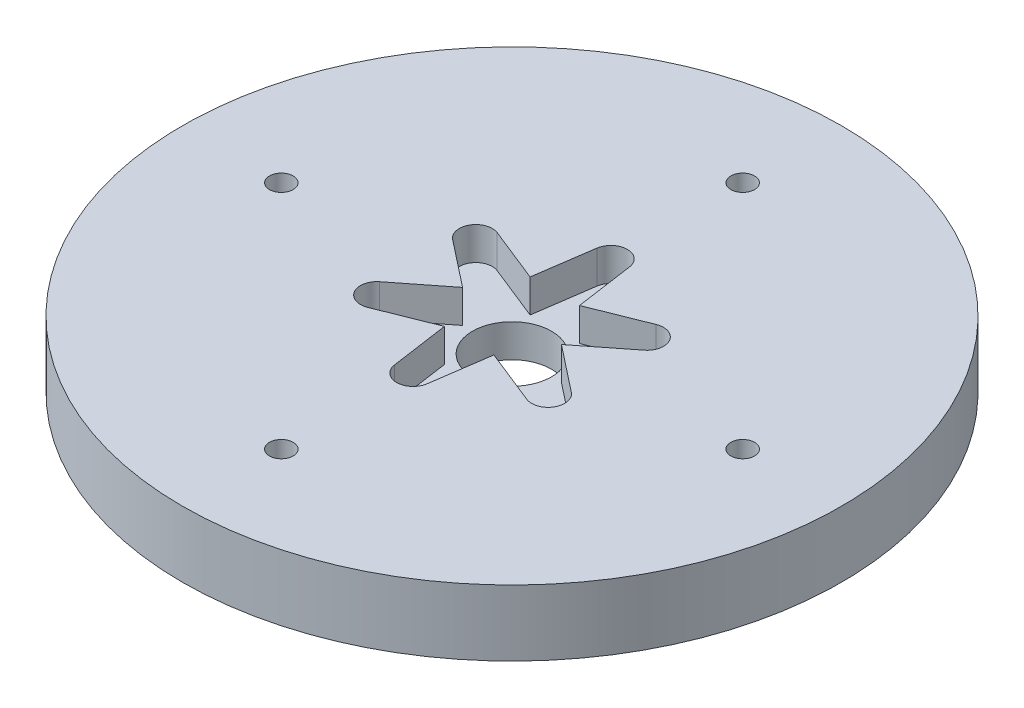
SolidWorks part; units mm, degrees
ref_plane "Front Plane" through (0, 0, 0) normal (0, 0, 1) x (1, 0, 0)
ref_plane "Top Plane" through (0, 0, 0) normal (0, 1, 0) x (1, 0, 0)
ref_plane "Right Plane" through (0, 0, 0) normal (1, 0, 0) x (0, 0, -1)
sketch "Sketch1" plane through (0, 0, 0) normal (0, 1, 0) x (1, 0, 0)
  line L0 (0, 0) -> (0, 15) construction
  line L1 (-3.75, 6.5) -> (3.75, 6.5) construction
  line L2 (-3.75, 6.5) -> (-2.4745, 15.3564)
  line L3 (2.4745, 15.3564) -> (3.75, 6.5)
  line L4 (14.5363, 5.5352) -> (7.5042, 0.0024)
  line L5 (3.7542, 6.4976) -> (12.0618, 9.8211)
  line L6 (12.0618, -9.8211) -> (3.7542, -6.4976)
  line L7 (7.5042, -0.0024) -> (14.5363, -5.5352)
  line L8 (-2.4745, -15.3564) -> (-3.75, -6.5)
  line L9 (3.75, -6.5) -> (2.4745, -15.3564)
  line L10 (-14.5363, -5.5352) -> (-7.5042, -0.0024)
  line L11 (-3.7542, -6.4976) -> (-12.0618, -9.8211)
  line L12 (-12.0618, 9.8211) -> (-3.7542, 6.4976)
  line L13 (-7.5042, 0.0024) -> (-14.5363, 5.5352)
  line L14 (3.75, 6.5) -> (3.7542, 6.4976)
  line L15 (7.5042, 0.0024) -> (7.5042, -0.0024)
  line L16 (3.7542, -6.4976) -> (3.75, -6.5)
  line L17 (-3.75, -6.5) -> (-3.7542, -6.4976)
  line L18 (-7.5042, 0.0024) -> (-7.5042, -0.0024)
  line L19 (-3.75, 6.5) -> (-3.7542, 6.4976)
  arc A0 (2.4745, 15.3564) -> (-2.4745, 15.3564) centre (0, 15) ccw
  arc A1 (14.5363, 5.5352) -> (12.0618, 9.8211) centre (12.9904, 7.5) ccw
  arc A2 (12.0618, -9.8211) -> (14.5363, -5.5352) centre (12.9904, -7.5) ccw
  arc A3 (-2.4745, -15.3564) -> (2.4745, -15.3564) centre (0, -15) ccw
  arc A4 (-14.5363, -5.5352) -> (-12.0618, -9.8211) centre (-12.9904, -7.5) ccw
  arc A5 (-12.0618, 9.8211) -> (-14.5363, 5.5352) centre (-12.9904, 7.5) ccw
  circle A7 centre (0, 0) radius 50
  circle A8 centre (0, 35) radius 1.8
  circle A9 centre (35, 0) radius 1.8
  circle A10 centre (0, -35) radius 1.8
  circle A11 centre (-35, 0) radius 1.8
  point P5 (0, 6.5)
  point P35 (0, 0)
  point P46 (0, 0)
  dimension "D4" = 5
  dimension "D6" = 100
  dimension "D7" = 3.6
  dimension "D1" = 15
  dimension "D2" = 7.5
  dimension "D3" = 6.5
  dimension "D8" = 35
  dimension "D5" = 6
  dimension "D9" = 4
extrude "Boss-Extrude1" add sketch "Sketch1" along normal blind 5
sketch "Sketch2" plane through (0, 0, 0) normal (0, -1, 0) x (1, 0, 0)
  circle A0 centre (0, 0) radius 50
  circle A1 centre (0, 0) radius 50 construction
  circle A2 centre (-35, 0) radius 1.8
  circle A3 centre (0, 35) radius 1.8
  circle A4 centre (35, 0) radius 1.8
  circle A5 centre (0, -35) radius 1.8
  circle A6 centre (0, -35) radius 1.8 construction
  circle A7 centre (35, 0) radius 1.8 construction
  circle A8 centre (0, 35) radius 1.8 construction
  circle A9 centre (-35, 0) radius 1.8 construction
  circle A10 centre (0, 0) radius 6
  dimension "D1" = 12
extrude "Boss-Extrude2" add sketch "Sketch2" along normal blind 5
